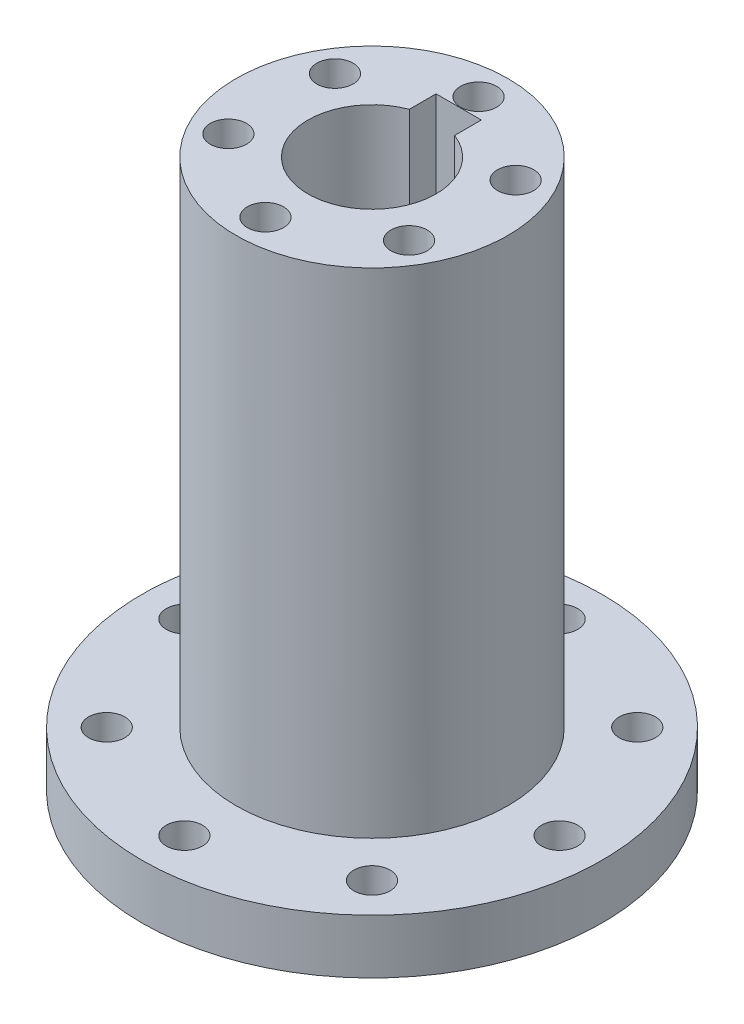
SolidWorks part; units mm, degrees
material "Alloy Steel"
ref_plane "Front Plane" through (0, 0, 0) normal (0, 0, 1) x (1, 0, 0)
ref_plane "Top Plane" through (0, 0, 0) normal (0, 1, 0) x (1, 0, 0)
ref_plane "Right Plane" through (0, 0, 0) normal (1, 0, 0) x (0, 0, -1)
sketch "Sketch2" plane through (0, 0, 0) normal (0, 1, 0) x (1, 0, 0)
  circle A0 centre (0, 0) radius 25.4
  dimension "D1" = 50.8
extrude "Boss-Extrude2" add sketch "Sketch2" along normal blind 6
sketch "Sketch3" plane through (0, 0, 0) normal (0, -1, 0) x (1, 0, 0)
  circle A0 centre (0, 0) radius 15
  dimension "D1" = 30
extrude "Boss-Extrude3" add sketch "Sketch3" against normal blind 60.5
sketch "Sketch4" plane through (0, 0, 0) normal (0, -1, 0) x (1, 0, 0)
  circle A0 centre (0, 0) radius 10.315
  dimension "D1" = 20.63
extrude "Cut-Extrude1" cut sketch "Sketch4" against normal blind 38.1
sketch "Sketch5" plane through (0, 38.1, 0) normal (0, -1, 0) x (1, 0, 0)
  circle A0 centre (0, 0) radius 7.07
  point P8 (0, 9.0532)
  dimension "D1" = 14.14
extrude "Cut-Extrude2" cut sketch "Sketch5" against normal through all
hole_wizard "Ø4.0mm Dowel Hole1" positions "Sketch9" profile "Sketch10" hole size "Ø4.0" standard "ANSI Metric" end condition through all
sketch "Sketch9" plane through (0, 0, 0) normal (0, -1, 0) x (-1, 0, 0)
  point P0 (0, 20.7)
  dimension "D1" = 20.7
sketch "Sketch10" plane through (0, 0, -20.7) normal (1, 0, 0) x (0, 0, -1)
  line L0 (0, 0) -> (0, 60.5)
  line L1 (0, 60.5) -> (2, 60.5)
  line L2 (2, 60.5) -> (2, 0)
  line L5 (2, 0) -> (0, 0)
  line L11 (0, -6.35) -> (0, 107.95) construction
  dimension "Thru Hole Dia." = 4
  dimension "Thru Hole Depth" = 60.5
pattern_circular "CirPattern1" count 8 over 360 about axis through (0, 0, 0) along (0, 1, 0) of "Ø4.0mm Dowel Hole1"
hole_wizard "Ø3.0mm Dowel Hole1" positions "Sketch12" profile "Sketch13" hole size "Ø3.0" standard "ANSI Metric"
sketch "Sketch12" plane through (0, 60.5, 0) normal (0, 1, 0) x (1, 0, 0)
  point P0 (-10.14, -5.71)
  dimension "D1" = 10.14
  dimension "D2" = 5.71
sketch "Sketch13" plane through (-10.14, 60.5, 5.71) normal (1, 0, 0) x (0, 0, 1)
  line L0 (0, 0) -> (0, 6.2017)
  line L1 (0, 6.2017) -> (2, 5)
  line L2 (2, 5) -> (2, 0)
  line L5 (2, 0) -> (0, 0)
  line L10 (0, 6.2017) -> (-2, 5) construction
  line L11 (0, -6.35) -> (0, 107.95) construction
  dimension "Hole Dia." = 4
  dimension "Hole Depth" = 5
  dimension "Drill Angle" = 118
pattern_circular "CirPattern2" count 6 over 360 about axis through (0, 0, 0) along (0, 1, 0) of "Ø3.0mm Dowel Hole1"
sketch "Sketch14" plane through (0, 60.5, 0) normal (0, 1, 0) x (1, 0, 0)
  line L0 (0, 9.57) -> (0, 0) construction
  line L1 (-2.5, 9.57) -> (2.5, 9.57)
  line L2 (-2.5, 9.57) -> (-2.5, 6.6132)
  line L4 (2.5, 9.57) -> (2.5, 6.6132)
  line L5 (-2.5, 9.57) -> (0, 7.07) construction
  line L6 (0, 7.07) -> (2.5, 9.57) construction
  circle A0 centre (0, 0) radius 7.07 construction
  arc A1 (2.5, 6.6132) -> (-2.5, 6.6132) centre (0, 0) ccw
  point P0 (0, 7.07)
  dimension "D1" = 5
  dimension "D2" = 2.9568
extrude "Cut-Extrude3" cut sketch "Sketch14" against normal up to next
